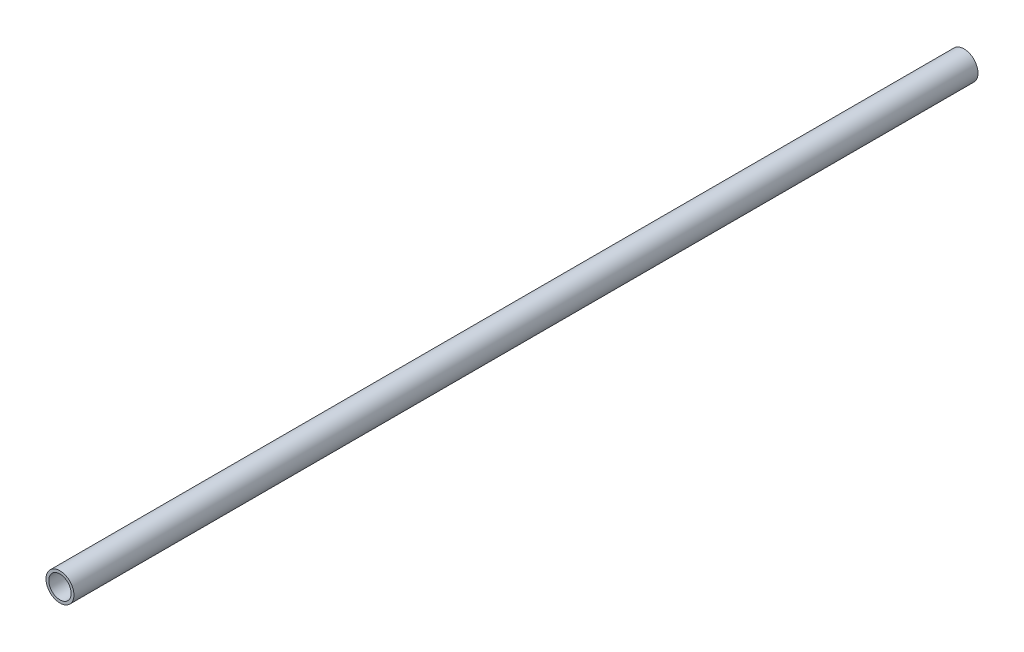
SolidWorks part; units mm, degrees
ref_plane "Ön Düzlem" through (0, 0, 0) normal (0, 0, 1) x (1, 0, 0)
ref_plane "Üst Düzlem" through (0, 0, 0) normal (0, 1, 0) x (1, 0, 0)
ref_plane "Sağ Düzlem" through (0, 0, 0) normal (1, 0, 0) x (0, 0, -1)
sketch "Çizim1" plane through (0, 0, 0) normal (0, 0, 1) x (1, 0, 0)
  circle A0 centre (0, 0) radius 2.5
  dimension "D1" = 5
extrude "Yükseklik-Ekstrüzyon1" add sketch "Çizim1" along normal blind 161.5
sketch "Çizim2" plane through (0, 0, 161.5) normal (0, 0, 1) x (1, 0, 0)
  circle A0 centre (0, 0) radius 2
  dimension "D1" = 4
extrude "Kes-Ekstrüzyon1" cut sketch "Çizim2" against normal blind 200
